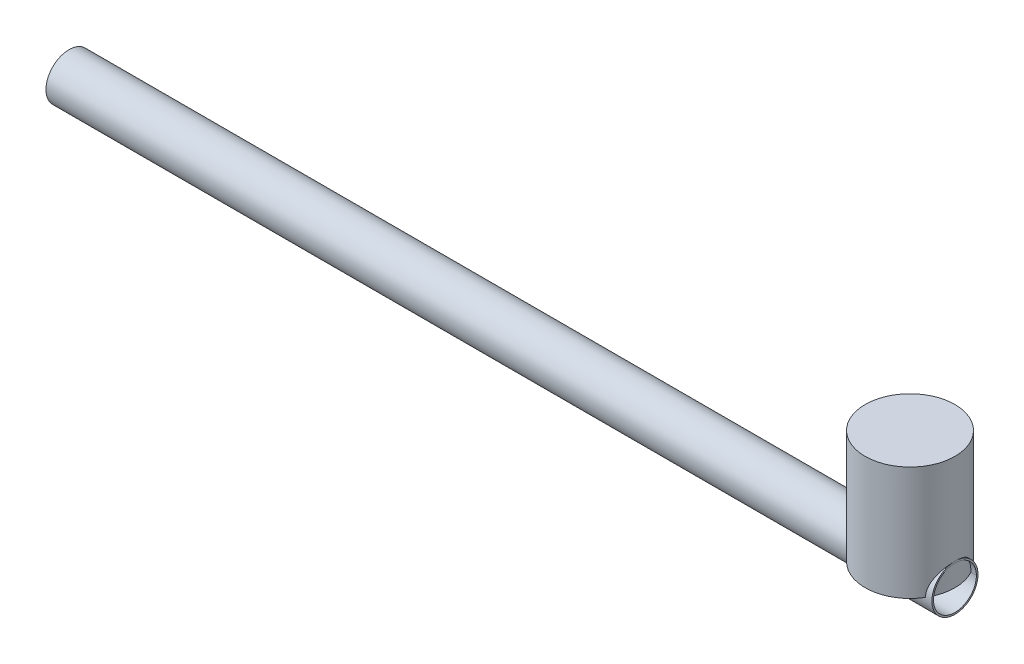
SolidWorks part; units mm, degrees
ref_plane "Front Plane" through (0, 0, 0) normal (0, 0, 1) x (1, 0, 0)
ref_plane "Top Plane" through (0, 0, 0) normal (0, 1, 0) x (1, 0, 0)
ref_plane "Right Plane" through (0, 0, 0) normal (1, 0, 0) x (0, 0, -1)
sketch "Sketch1" plane through (0, 0, 0) normal (1, 0, 0) x (0, 0, -1)
  circle A0 centre (0, 0) radius 12.7
  circle A1 centre (0, 0) radius 11.811
extrude "Boss-Extrude1" add sketch "Sketch1" along normal blind 488.039
sketch "Sketch2" plane through (0, 0, 0) normal (0, 1, 0) x (1, 0, 0)
  circle A0 centre (463.2998, 0) radius 24.7392
extrude "Boss-Extrude2" add sketch "Sketch2" along normal blind 62.7
